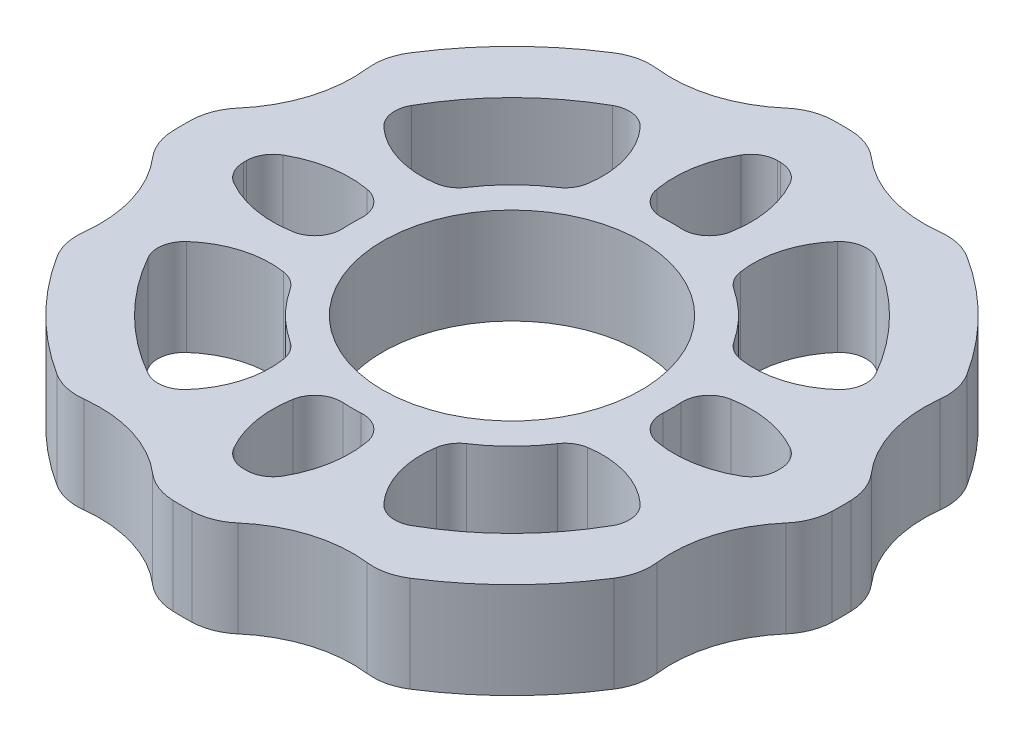
SolidWorks part; units mm, degrees
ref_plane "Ebene vorne" through (0, 0, 0) normal (0, 0, 1) x (1, 0, 0)
ref_plane "Ebene oben" through (0, 0, 0) normal (0, 1, 0) x (1, 0, 0)
ref_plane "Ebene rechts" through (0, 0, 0) normal (1, 0, 0) x (0, 0, -1)
sketch "Skizze1" plane through (0, 0, 0) normal (0, 1, 0) x (1, 0, 0)
  circle A0 centre (0, 0) radius 61.75
  dimension "D1" = 123.5
extrude "Aufsatz-Linear austragen1" add sketch "Skizze1" along normal blind 18
sketch "Skizze2" plane through (0, 18, 0) normal (0, 1, 0) x (1, 0, 0)
  line L0 (0, 0) -> (0, 77.47) construction
  line L1 (-23.68, 77.47) -> (23.68, 77.47) construction
  circle A0 centre (23.68, 77.47) radius 24
  circle A1 centre (-23.68, 77.47) radius 24
  circle M5 centre (0, 0) radius 61.75
  dimension "D1" = 48
  dimension "D2" = 47.36
  dimension "D3" = 77.47
extrude "Schnitt-Linear austragen1" cut sketch "Skizze2" against normal through all contours A1 M5 | A0 M5
fillet "Verrundung1" radius 10 4 edges at (29.577, 9, -54.2057) (5.7838, 9, -61.4785) (-5.7838, 9, -61.4785) (-29.577, 9, -54.2057)
sketch "Skizze5" plane through (0, 18, 0) normal (0, 1, 0) x (1, 0, 0)
  line L0 (-12.77, 37.56) -> (12.77, 37.56) construction
  line L1 (0, 37.56) -> (0, 0) construction
  arc A0 (2.9596, 49.9123) -> (-2.9596, 49.9123) centre (0, 0) ccw
  arc A1 (5.528, 29.4863) -> (-5.528, 29.4863) centre (0, 0) ccw
  arc A3 (-2.9596, 49.9123) -> (-5.528, 29.4863) centre (12.77, 37.56) ccw
  arc A6 (5.528, 29.4863) -> (2.9596, 49.9123) centre (-12.77, 37.56) ccw
  dimension "D1" = 100
  dimension "D2" = 60
  dimension "D3" = 20
  dimension "D4" = 25.54
  dimension "D5" = 37.56
extrude "Schnitt-Linear austragen3" cut sketch "Skizze5" against normal through all
sketch "Skizze6" plane through (0, 18, 0) normal (0, 1, 0) x (1, 0, 0)
  circle A0 centre (0, 0) radius 24.2
  dimension "D1" = 48.4
extrude "Schnitt-Linear austragen4" cut sketch "Skizze6" against normal through all
pattern_circular "Kreismuster1" count 4 over 360 about axis through (0, 0, 0) along (0, 1, 0) of "Schnitt-Linear austragen3", "Schnitt-Linear austragen1", "Verrundung1"
sketch "Skizze7" plane through (0, 18, 0) normal (0, 1, 0) x (1, 0, 0)
  line L0 (-43.6638, 43.6638) -> (0, 0) construction
  arc A0 (-33.0588, 52.1553) -> (-52.1553, 33.0588) centre (0, 0) ccw construction
  arc A2 (-14.885, 26.0468) -> (-21.5064, 45.1384) centre (-31.1127, 31.1127) ccw
  arc A3 (-14.885, 26.0468) -> (-26.0468, 14.885) centre (0, 0) ccw
  arc A4 (-21.5064, 45.1384) -> (-45.1384, 21.5064) centre (0, 0) ccw
  arc A5 (2.9596, 49.9123) -> (-2.9596, 49.9123) centre (0, 0) ccw construction
  arc A6 (5.528, 29.4863) -> (-5.528, 29.4863) centre (0, 0) ccw construction
  arc A7 (-45.1384, 21.5064) -> (-26.0468, 14.885) centre (-31.1127, 31.1127) ccw
  dimension "D1" = 34
  dimension "D2" = 44
extrude "Schnitt-Linear austragen5" cut sketch "Skizze7" against normal through all
fillet "Verrundung2" radius 5 20 edges at (-5.528, 9, -29.4863) (-2.9596, 9, -49.9123) (2.9596, 9, -49.9123) (5.528, 9, -29.4863) (-26.0468, 9, -14.885) (-14.885, 9, -26.0468) (-21.5064, 9, -45.1384) (-45.1384, 9, -21.5064) (2.9596, 9, 49.9123) (-2.9596, 9, 49.9123) (-5.528, 9, 29.4863) (5.528, 9, 29.4863) (49.9123, 9, 2.9596) (49.9123, 9, -2.9596) (29.4863, 9, -5.528) (29.4863, 9, 5.528) (-49.9123, 9, 2.9596) (-29.4863, 9, 5.528) (-29.4863, 9, -5.528) (-49.9123, 9, -2.9596)
pattern_circular "Kreismuster2" count 4 over 360 about axis through (0, 0, 0) along (0, 1, 0) of "Verrundung2", "Schnitt-Linear austragen5"
scale "Skalieren1" scale about centroid uniform scaling yes scale factor 0.13
